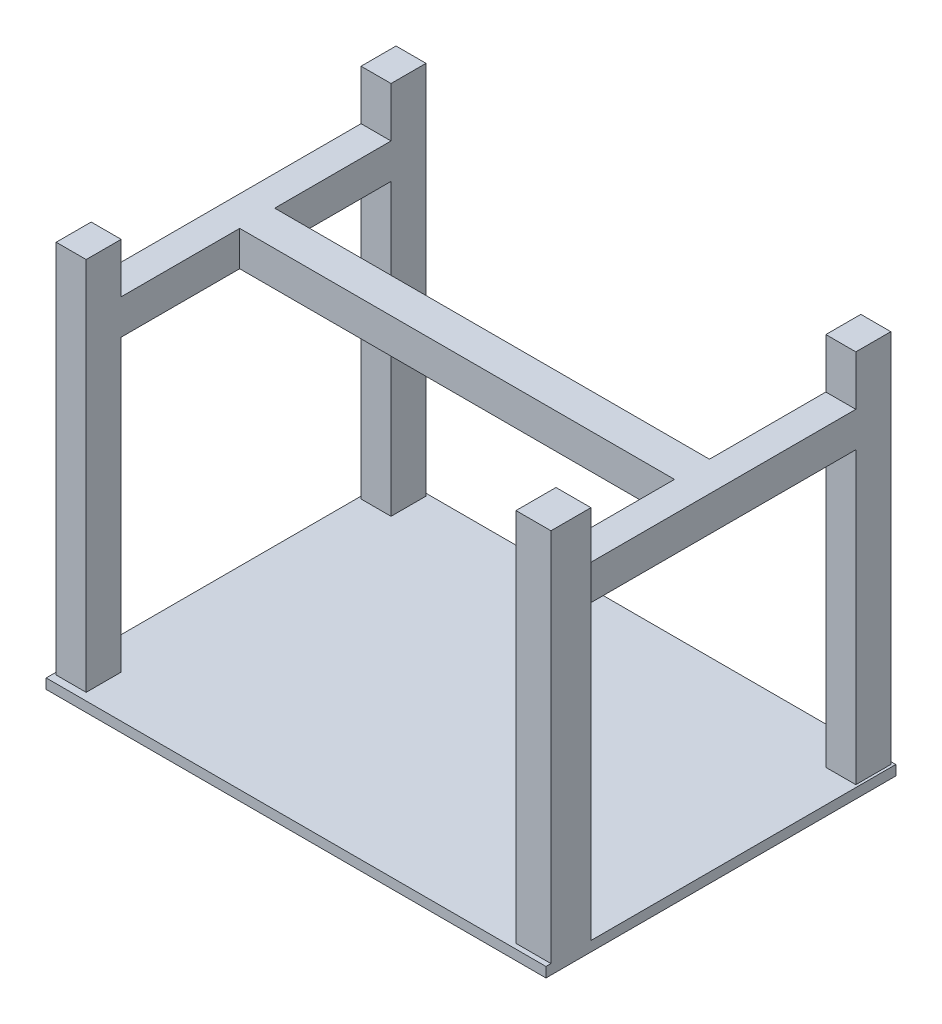
SolidWorks part; units mm, degrees
ref_plane "Front Plane" through (0, 0, 0) normal (0, 0, 1) x (1, 0, 0)
ref_plane "Top Plane" through (0, 0, 0) normal (0, 1, 0) x (1, 0, 0)
ref_plane "Right Plane" through (0, 0, 0) normal (1, 0, 0) x (0, 0, -1)
sketch "Sketch1" plane through (0, 0, 0) normal (0, 1, 0) x (1, 0, 0)
  line L1 (-1000, 700) -> (1000, 700)
  line L2 (-1000, 700) -> (-1000, -700)
  line L3 (-1000, -700) -> (1000, -700)
  line L4 (1000, 700) -> (1000, -700)
  line L5 (-1000, 700) -> (1000, -700) construction
  line L6 (-1000, -700) -> (1000, 700) construction
  point P0 (0, 0)
  dimension "D1" = 2000
  dimension "D2" = 1400
extrude "Boss-Extrude1" add sketch "Sketch1" along normal blind 40
sketch "Sketch4" plane through (0, 40, 0) normal (0, 1, 0) x (1, 0, 0)
  line L0 (1000, 0) -> (-1000, 0) construction
  line L1 (-1000, 700) -> (-1000, -700) construction
  line L2 (0, -700) -> (0, 700) construction
  line L3 (1000, 700) -> (-1000, 700) construction
  line L4 (1000, 10) -> (-1000, 10)
  line L5 (-1000, 700) -> (-860, 700)
  line L6 (-1000, 700) -> (-1000, 540)
  line L7 (-1000, 540) -> (-860, 540)
  line L8 (-860, 700) -> (-860, 540)
  line L9 (-990, 690) -> (-990, 550)
  line L10 (-990, 550) -> (-870, 550)
  line L11 (-870, 690) -> (-870, 550)
  line L12 (-990, 690) -> (-870, 690)
  line L13 (-990, -670) -> (-870, -670)
  line L14 (-870, -670) -> (-870, -530)
  line L15 (-990, -530) -> (-870, -530)
  line L16 (-990, -670) -> (-990, -530)
  line L17 (-860, -680) -> (-860, -520)
  line L18 (-1000, -520) -> (-860, -520)
  line L19 (-1000, -680) -> (-1000, -520)
  line L20 (-1000, -680) -> (-860, -680)
  line L21 (1000, -680) -> (860, -680)
  line L22 (1000, -680) -> (1000, -520)
  line L23 (1000, -520) -> (860, -520)
  line L24 (860, -680) -> (860, -520)
  line L25 (990, -670) -> (990, -530)
  line L26 (990, -530) -> (870, -530)
  line L27 (870, -670) -> (870, -530)
  line L28 (990, -670) -> (870, -670)
  line L29 (990, 690) -> (870, 690)
  line L30 (870, 690) -> (870, 550)
  line L31 (990, 550) -> (870, 550)
  line L32 (990, 690) -> (990, 550)
  line L33 (860, 700) -> (860, 540)
  line L34 (1000, 540) -> (860, 540)
  line L35 (1000, 700) -> (1000, 540)
  line L36 (1000, 700) -> (860, 700)
  point P6 (0, 0)
  point P12 (0, 0)
  dimension "D1" = 140
  dimension "D2" = 160
  dimension "D3" = 10
  dimension "D4" = 10
extrude "Boss-Extrude2" add sketch "Sketch4" along normal blind 1500 contours L16 L13 L14 L15 | L32 L31 L30 L29 | L24 L23 L22 L21 | L9 L10 L11 L12
sketch "Sketch5" plane through (0, 0, 670) normal (0, 0, 1) x (1, 0, 0)
  line L0 (-990, 1540) -> (-990, 40) construction
  line L1 (-990, 1340.8317) -> (-870, 1340.8317)
  line L2 (-990, 1340.8317) -> (-990, 1200.8317)
  line L3 (-990, 1200.8317) -> (-870, 1200.8317)
  line L4 (-870, 1340.8317) -> (-870, 1200.8317)
  line L5 (-870, 1540) -> (-870, 40) construction
  line L6 (0, -727.6765) -> (0, 727.6765) construction
  line L8 (870, 1340.8317) -> (870, 1200.8317)
  line L9 (990, 1200.8317) -> (870, 1200.8317)
  line L10 (990, 1340.8317) -> (990, 1200.8317)
  line L11 (990, 1340.8317) -> (870, 1340.8317)
  point P12 (0, 0)
  dimension "D1" = 140
extrude "Boss-Extrude3" add sketch "Sketch5" against normal up to surface (1220 mm away) up to face at (930, 790, -550)
sketch "Sketch6" plane through (870, 0, 0) normal (-1, 0, 0) x (0, 0, 1)
  line L0 (-550, 1340.8317) -> (530, 1340.8317) construction
  line L1 (-84.3483, 1340.8317) -> (55.6517, 1340.8317)
  line L2 (-84.3483, 1340.8317) -> (-84.3483, 1200.8317)
  line L3 (-84.3483, 1200.8317) -> (55.6517, 1200.8317)
  line L4 (55.6517, 1340.8317) -> (55.6517, 1200.8317)
  line L5 (-550, 1200.8317) -> (530, 1200.8317) construction
  dimension "D1" = 140
extrude "Boss-Extrude4" add sketch "Sketch6" along normal up to surface (1740 mm away) up to face at (-870, 950.2772, -10)
